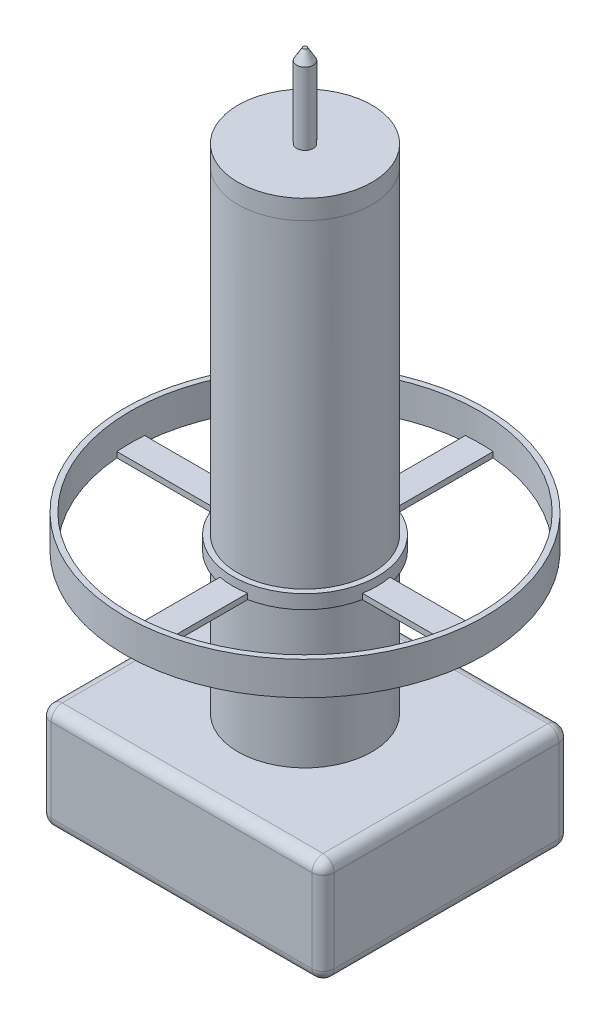
SolidWorks part; units mm, degrees
ref_plane "Front Plane" through (0, 0, 0) normal (0, 0, 1) x (1, 0, 0)
ref_plane "Top Plane" through (0, 0, 0) normal (0, 1, 0) x (1, 0, 0)
ref_plane "Right Plane" through (0, 0, 0) normal (1, 0, 0) x (0, 0, -1)
sketch "Board" plane through (0, 0, 0) normal (0, 1, 0) x (1, 0, 0)
  line L1 (-42.5, -42.5) -> (42.5, -42.5)
  line L2 (-42.5, -42.5) -> (-42.5, 42.5)
  line L3 (-42.5, 42.5) -> (42.5, 42.5)
  line L4 (42.5, -42.5) -> (42.5, 42.5)
  line L5 (-42.5, -42.5) -> (42.5, 42.5) construction
  line L6 (-42.5, 42.5) -> (42.5, -42.5) construction
  circle A0 centre (-38.5, 38.5) radius 1.6
  circle A1 centre (38.5, 38.5) radius 1.6
  circle A2 centre (-38.5, -38.5) radius 1.6
  circle A3 centre (38.5, -38.5) radius 1.6
  point P0 (0, 0)
  point P14 (0, 0)
  point P15 (0, 0)
  point P16 (0, 0)
  point P17 (32.2183, -32.2183)
  dimension "D3" = 3.2
  dimension "D1" = 85
  dimension "D2" = 85
  dimension "D4" = 4
sketch "Sketch2" plane through (0, 0, 0) normal (0, 1, 0) x (1, 0, 0)
  line L0 (-42.5, -42.5) -> (42.5, -42.5) construction
  line L1 (-44.5, 44.5) -> (57.5, 44.5)
  line L2 (-44.5, 44.5) -> (-44.5, -44.5)
  line L3 (-44.5, -44.5) -> (57.5, -44.5)
  line L4 (57.5, 44.5) -> (57.5, -44.5)
  line L5 (-42.5, -42.5) -> (-42.5, 42.5) construction
  line L6 (-42.5, 42.5) -> (42.5, 42.5) construction
  line L7 (42.5, -42.5) -> (42.5, 42.5) construction
  dimension "D1" = 2
  dimension "D2" = 2
  dimension "D3" = 2
  dimension "D4" = 15
extrude "Boss-Extrude1" add sketch "Sketch2" along normal blind 38
sketch "Sketch3" plane through (0, 38, 0) normal (0, 1, 0) x (1, 0, 0)
  line L1 (57.5, 44.5) -> (-44.5, 44.5) construction
  line L2 (6.5, 44.5) -> (6.5, 0) construction
  circle A0 centre (6.5, 0) radius 24.13
  point P4 (6.5, 44.5)
  dimension "D1" = 48.26
extrude "Boss-Extrude2" add sketch "Sketch3" along normal blind 177.8
sketch "Sketch4" plane through (0, 38, 0) normal (0, 1, 0) x (1, 0, 0)
  circle A0 centre (6.5, 0) radius 65
  circle A1 centre (6.5, 0) radius 63
  dimension "D1" = 130
  dimension "D2" = 2
extrude "Boss-Extrude3" add sketch "Sketch4" along normal blind 12 from offset 50.8 separate body
sketch "Sketch5" plane through (0, 88.8, 0) normal (0, -1, 0) x (1, 0, 0)
  line L0 (1.5, 23.6063) -> (1.5, 62.8013)
  line L1 (11.5, 62.8013) -> (11.5, 23.6063)
  line L2 (69.3013, -5) -> (30.1063, -5)
  line L3 (30.1063, 5) -> (69.3013, 5)
  line L4 (1.5, -62.8013) -> (1.5, -23.6063)
  line L5 (11.5, -23.6063) -> (11.5, -62.8013)
  line L6 (-56.3013, 5) -> (-17.1063, 5)
  line L7 (-17.1063, -5) -> (-56.3013, -5)
  circle A0 centre (6.5, 0) radius 24.13 construction
  circle A1 centre (6.5, 0) radius 24.13 construction
  circle A2 centre (6.5, 0) radius 63 construction
  arc A3 (1.5, 23.6063) -> (11.5, 23.6063) centre (6.5, 0) cw
  arc A4 (1.5, 62.8013) -> (11.5, 62.8013) centre (6.5, 0) cw
  arc A5 (69.3013, 5) -> (69.3013, -5) centre (6.5, 0) cw
  arc A6 (30.1063, 5) -> (30.1063, -5) centre (6.5, 0) cw
  arc A7 (11.5, -62.8013) -> (1.5, -62.8013) centre (6.5, 0) cw
  arc A8 (11.5, -23.6063) -> (1.5, -23.6063) centre (6.5, 0) cw
  arc A9 (-56.3013, -5) -> (-56.3013, 5) centre (6.5, 0) cw
  arc A10 (-17.1063, -5) -> (-17.1063, 5) centre (6.5, 0) cw
  point P26 (6.5, 0)
  dimension "D1" = 10
  dimension "D2" = 4
extrude "Boss-Extrude4" add sketch "Sketch5" against normal blind 2
sketch "Sketch7" plane through (0, 88.8, 0) normal (0, -1, 0) x (1, 0, 0)
  circle A0 centre (6.5, 0) radius 24.13 construction
  circle A1 centre (6.5, 0) radius 24.13
  circle A2 centre (6.5, 0) radius 26.13
  dimension "D1" = 2
extrude "Boss-Extrude6" add sketch "Sketch7" against normal blind 5
sketch "Sketch6" plane through (0, 215.8, 0) normal (0, 1, 0) x (1, 0, 0)
  circle A0 centre (6.5, 0) radius 3
  dimension "D1" = 6
extrude "Boss-Extrude5" add sketch "Sketch6" along normal blind 30
chamfer "Chamfer1" distance 4 angle 30 1 edges at (6.5, 245.8, 3)
ref_plane "Plane2" through (0, 208.8, 0) normal (0, 1, 0) x (1, 0, 0)
split line "Split Line2"
fillet "Fillet1" radius 4 12 edges at (-44.5, 38, 0) (-44.5, 0, 0) (6.5, 38, -44.5) (-44.5, 19, -44.5) (6.5, 0, -44.5) (57.5, 38, 0) (57.5, 19, -44.5) (57.5, 0, 0) (-44.5, 19, 44.5) (6.5, 38, 44.5) (57.5, 19, 44.5) (6.5, 0, 44.5)
